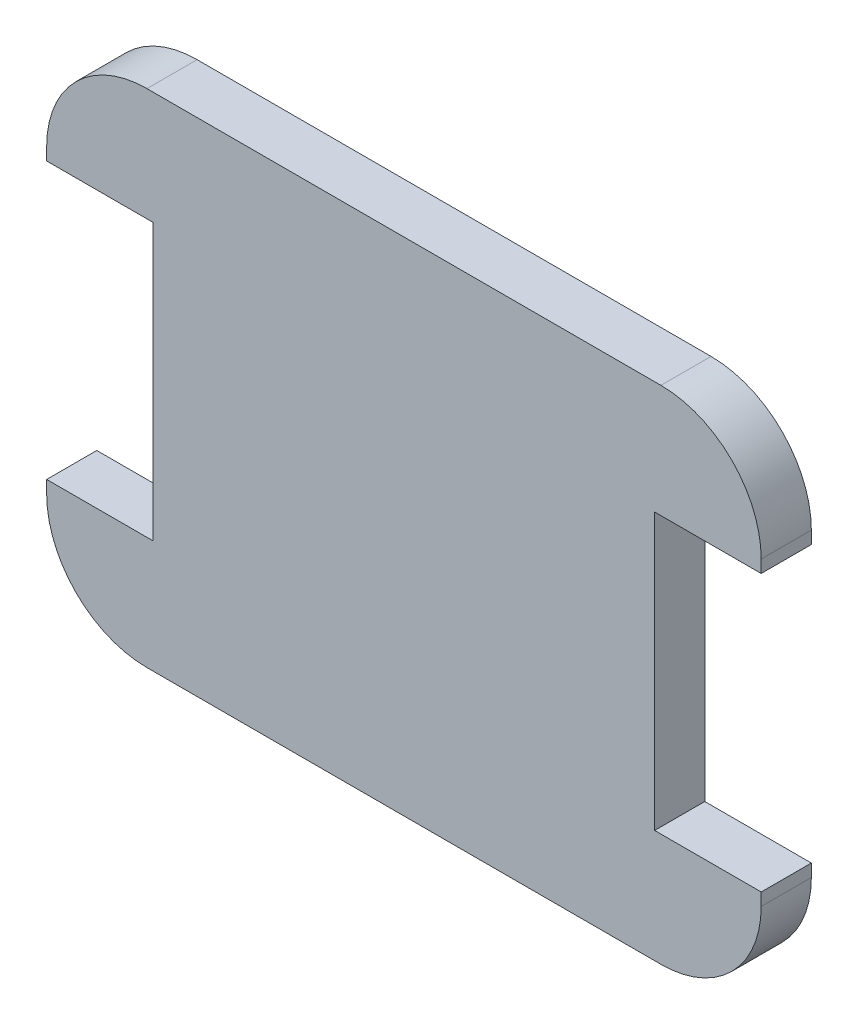
SolidWorks part; units mm, degrees
material "Thornel Mat VMA"
ref_plane "Alzado" through (0, 0, 0) normal (0, 0, 1) x (1, 0, 0)
ref_plane "Planta" through (0, 0, 0) normal (0, 1, 0) x (1, 0, 0)
ref_plane "Vista lateral" through (0, 0, 0) normal (1, 0, 0) x (0, 0, -1)
sketch "Croquis1" plane through (0, 0, 0) normal (0, 0, 1) x (1, 0, 0)
  line L1 (-5, -5) -> (5, -5)
  line L2 (-5, -5) -> (-5, 5)
  line L3 (-5, 5) -> (5, 5)
  line L4 (5, -5) -> (5, 5)
  line L5 (-5, -5) -> (5, 5) construction
  line L6 (-5, 5) -> (5, -5) construction
  point P0 (0, 0)
  dimension "D1" = 10
  dimension "D2" = 10
extrude "Saliente-Extruir1" add sketch "Croquis1" along normal blind 1
sketch "Croquis2" plane through (0, 0, 1) normal (0, 0, 1) x (1, 0, 0)
  line L0 (0, 0) -> (0, 5) construction
  line L1 (-5, 5) -> (-5.125, 5)
  line L2 (-5, 5) -> (-5, 2.75)
  line L3 (-5, 2.75) -> (-7.125, 2.75)
  line L4 (-7.125, 3) -> (-7.125, 2.75)
  line L5 (5, 5) -> (-5, 5) construction
  line L6 (0, 0) -> (5, 0) construction
  line L7 (5, -5) -> (5, 5) construction
  line L8 (5, 2.75) -> (7.125, 2.75)
  line L9 (7.125, 3) -> (7.125, 2.75)
  line L10 (5, 5) -> (5.125, 5)
  line L11 (5, 5) -> (5, 2.75)
  line L12 (5, -5) -> (5.125, -5)
  line L13 (5, -5) -> (5, -2.75)
  line L14 (5, -2.75) -> (7.125, -2.75)
  line L15 (7.125, -3) -> (7.125, -2.75)
  line L16 (-5, -2.75) -> (-7.125, -2.75)
  line L17 (-7.125, -3) -> (-7.125, -2.75)
  line L18 (-5, -5) -> (-5.125, -5)
  line L19 (-5, -5) -> (-5, -2.75)
  arc A0 (-5.125, 5) -> (-7.125, 3) centre (-5.125, 3) ccw
  arc A1 (5.125, 5) -> (7.125, 3) centre (5.125, 3) cw
  arc A2 (5.125, -5) -> (7.125, -3) centre (5.125, -3) ccw
  arc A3 (-5.125, -5) -> (-7.125, -3) centre (-5.125, -3) cw
  point P7 (-7.125, 5)
  dimension "D3" = 2
  dimension "D1" = 2.25
  dimension "D2" = 2.125
extrude "Saliente-Extruir2" add sketch "Croquis2" against normal through all
